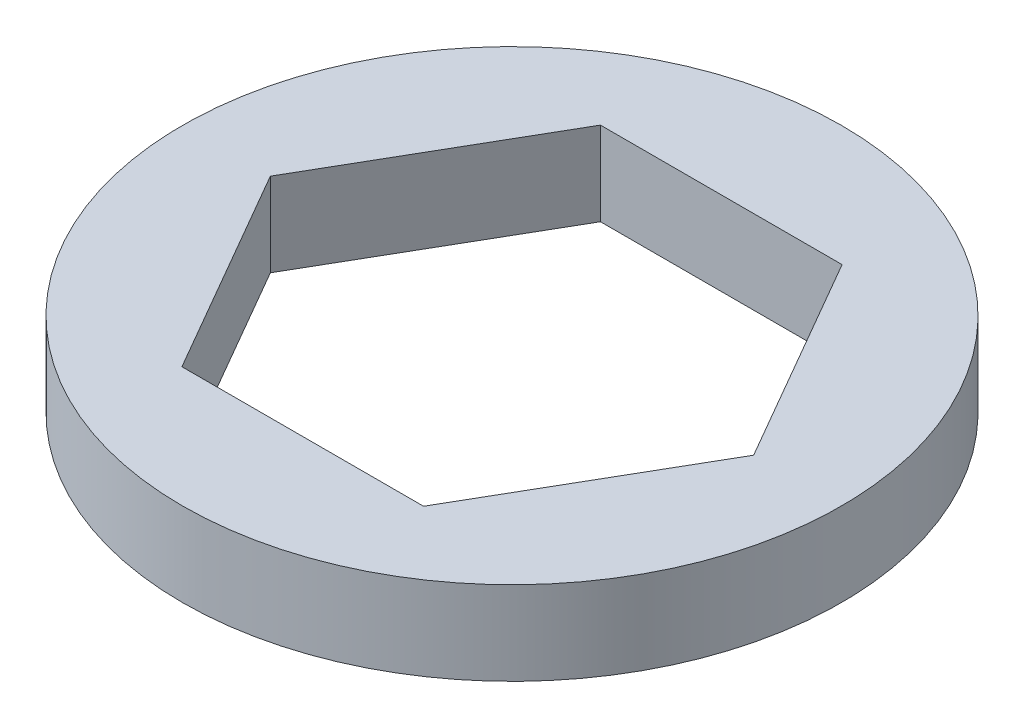
SolidWorks part; units mm, degrees
ref_plane "Front Plane" through (0, 0, 0) normal (0, 0, 1) x (1, 0, 0)
ref_plane "Top Plane" through (0, 0, 0) normal (0, 1, 0) x (1, 0, 0)
ref_plane "Right Plane" through (0, 0, 0) normal (1, 0, 0) x (0, 0, -1)
sketch "Sketch1" plane through (0, 0, 0) normal (0, 1, 0) x (1, 0, 0)
  line L1 (-7.3323, 0) -> (-3.6662, -6.35)
  line L2 (-3.6662, -6.35) -> (3.6662, -6.35)
  line L3 (3.6662, -6.35) -> (7.3323, 0)
  line L4 (7.3323, 0) -> (3.6662, 6.35)
  line L5 (3.6662, 6.35) -> (-3.6662, 6.35)
  line L6 (-3.6662, 6.35) -> (-7.3323, 0)
  circle A0 centre (0, 0) radius 10
  circle A1 centre (0, 0) radius 6.35 construction
  dimension "D2" = 20
  dimension "D1" = 12.7
extrude "Boss-Extrude1" add sketch "Sketch1" along normal blind 2.54
